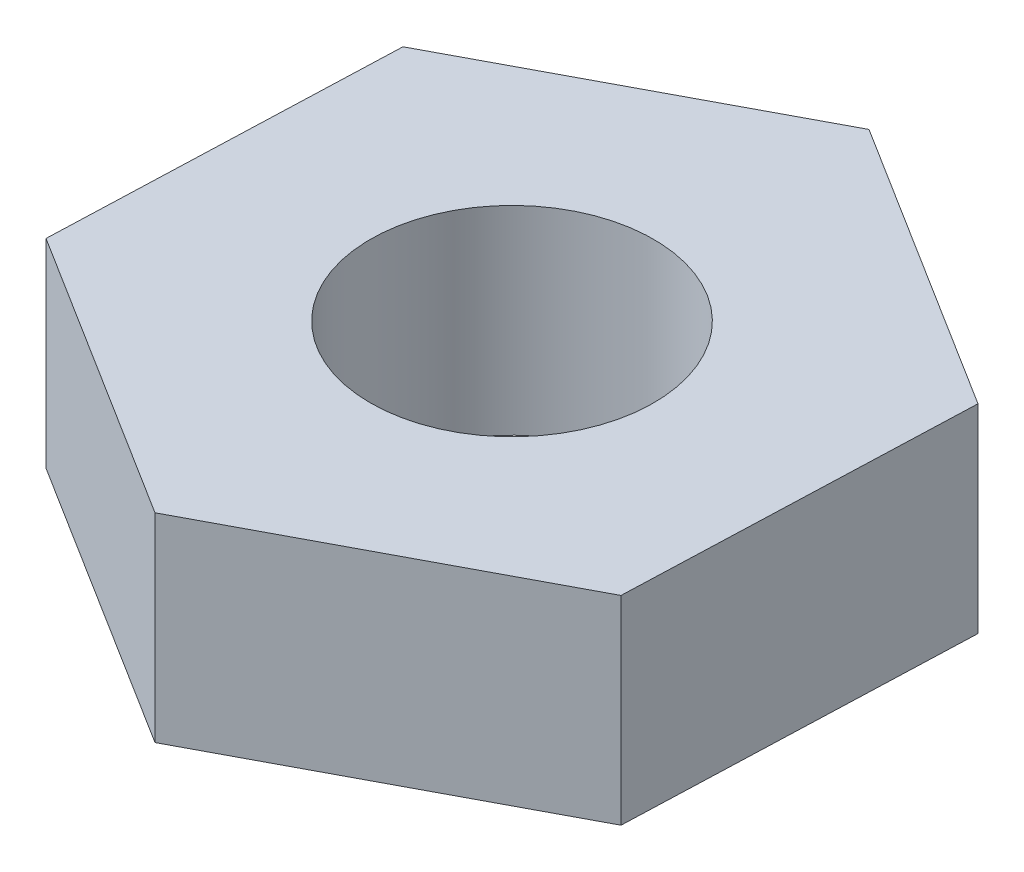
SolidWorks part; units mm, degrees
ref_plane "Front Plane" through (0, 0, 0) normal (0, 0, 1) x (1, 0, 0)
ref_plane "Top Plane" through (0, 0, 0) normal (0, 1, 0) x (1, 0, 0)
ref_plane "Right Plane" through (0, 0, 0) normal (1, 0, 0) x (0, 0, -1)
sketch "Sketch1" plane through (0, 0, 0) normal (0, 1, 0) x (1, 0, 0)
  line L1 (2.3298, -1.4603) -> (2.4296, 1.2875)
  line L2 (2.4296, 1.2875) -> (0.0998, 2.7478)
  line L3 (0.0998, 2.7478) -> (-2.3298, 1.4603)
  line L4 (-2.3298, 1.4603) -> (-2.4296, -1.2875)
  line L5 (-2.4296, -1.2875) -> (-0.0998, -2.7478)
  line L6 (-0.0998, -2.7478) -> (2.3298, -1.4603)
  circle A0 centre (0, 0) radius 2.3813 construction
  dimension "D1" = 4.7625
extrude "Boss-Extrude1" add sketch "Sketch1" along normal blind 1.5875
hole_wizard "#4-40 Tapped Hole1" positions "Sketch2" profile "Sketch4" tap size "#4-40" standard "ANSI Inch" end condition through all
sketch "Sketch2" plane through (0, 1.5875, 0) normal (0, 1, 0) x (1, 0, 0)
  line L0 (-2.3298, 1.4603) -> (2.3298, -1.4603) construction
  point P8 (0, 0)
sketch "Sketch4" plane through (0, 1.5875, 0) normal (1, 0, 0) x (0, 0, 1)
  line L0 (0, 0) -> (0, 1.5875)
  line L1 (0, 1.5875) -> (1.1303, 1.5875)
  line L2 (1.1303, 1.5875) -> (1.1303, 0)
  line L5 (1.1303, 0) -> (0, 0)
  line L11 (0, -6.35) -> (0, 107.95) construction
  dimension "Thru Tap Drill Dia." = 2.2606
  dimension "Thru Tap Drill Depth" = 1.5875
cosmetic thread "Hole Thread1"
